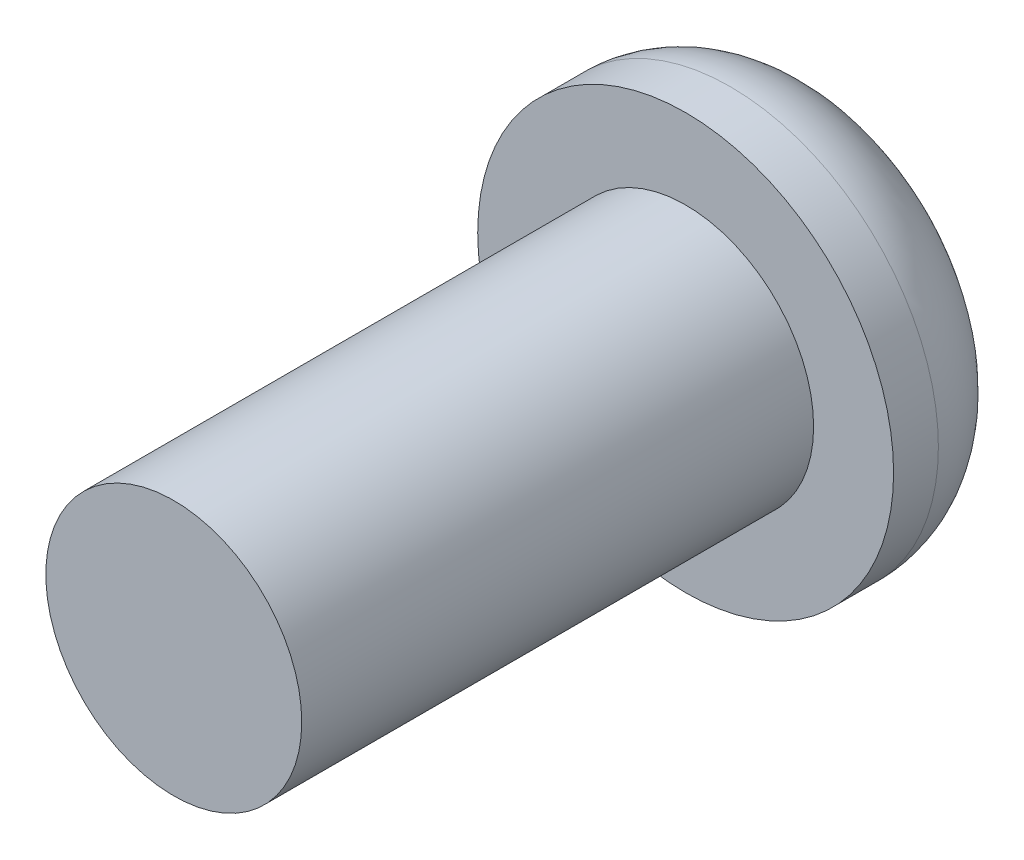
SolidWorks part; units mm, degrees
ref_plane "前视基准面" through (0, 0, 0) normal (0, 0, 1) x (1, 0, 0)
ref_plane "上视基准面" through (0, 0, 0) normal (0, 1, 0) x (1, 0, 0)
ref_plane "右视基准面" through (0, 0, 0) normal (1, 0, 0) x (0, 0, -1)
sketch "草图1" plane through (0, 0, 0) normal (0, 0, 1) x (1, 0, 0)
  circle A0 centre (0, 0) radius 2
extrude "凸台-拉伸1" add sketch "草图1" along normal blind 8
sketch "草图2" plane through (0, 0, 0) normal (0, 0, -1) x (-1, 0, 0)
  circle A0 centre (0, 0) radius 3.25
extrude "凸台-拉伸2" add sketch "草图2" along normal blind 2.2
fillet "圆角1" radius 1.5 1 edges at (-3.25, 0, -2.2)
